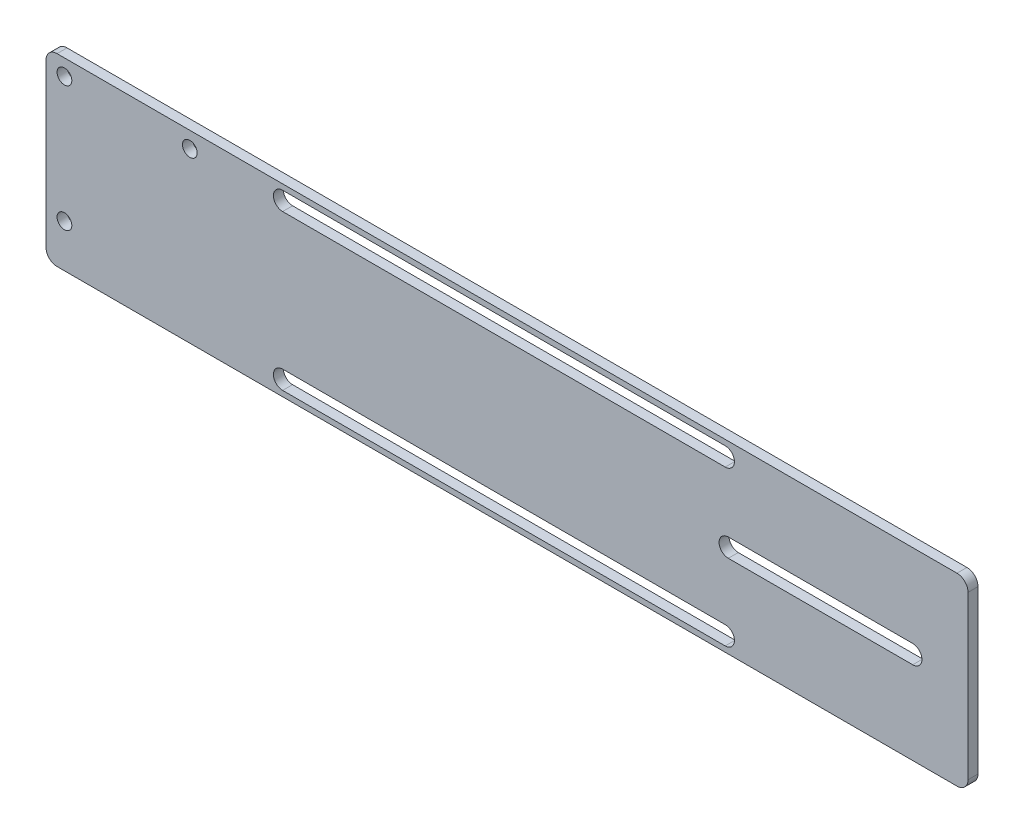
SolidWorks part; units mm, degrees
ref_plane "前视基准面" through (0, 0, 0) normal (0, 0, 1) x (1, 0, 0)
ref_plane "上视基准面" through (0, 0, 0) normal (0, 1, 0) x (1, 0, 0)
ref_plane "右视基准面" through (0, 0, 0) normal (1, 0, 0) x (0, 0, -1)
sketch "草图1" plane through (0, 0, 0) normal (0, 0, 1) x (1, 0, 0)
  line L0 (0, 22) -> (0, -22)
  line L1 (3, 25) -> (247, 25)
  line L3 (3, -25) -> (247, -25)
  line L4 (250, 22) -> (250, -22)
  line L9 (185, 2.5) -> (235, 2.5)
  line L10 (235, -2.5) -> (185, -2.5)
  line L11 (64.1586, 18.5) -> (184.1586, 18.5)
  line L13 (64.1586, 23.5) -> (184.1586, 23.5)
  line L15 (0, 0) -> (185, 0) construction
  line L16 (64.1586, -23.5) -> (184.1586, -23.5)
  line L17 (64.1586, -18.5) -> (184.1586, -18.5)
  arc A0 (250, -22) -> (247, -25) centre (247, -22) cw
  arc A1 (250, 22) -> (247, 25) centre (247, 22) ccw
  arc A2 (0, -22) -> (3, -25) centre (3, -22) ccw
  arc A3 (0, 22) -> (3, 25) centre (3, 22) cw
  circle A8 centre (5, 20.65) radius 2
  circle A9 centre (39, 20.65) radius 2
  circle A10 centre (5, -13.35) radius 2
  circle A11 centre (185, 0) radius 2.5
  circle A12 centre (235, 0) radius 2.5
  circle A13 centre (64.1586, 21) radius 2.5
  circle A14 centre (184.1586, 21) radius 2.5
  circle A15 centre (184.1586, -21) radius 2.5
  circle A16 centre (64.1586, -21) radius 2.5
  dimension "D1" = 3
  dimension "D2" = 5
  dimension "D3" = 5
  dimension "D4" = 15
  dimension "D7" = 5
  dimension "D9" = 5
  dimension "D5" = 50
  dimension "D6" = 250
  dimension "D8" = 21
  dimension "D10" = 21
  dimension "D11" = 120
extrude "凸台-拉伸1" add sketch "草图1" along normal blind 2.7 contours A3 L0 A2 L3 A0 L4 A1 L1 A12 L10 A11 L9 A10 A9 A8
